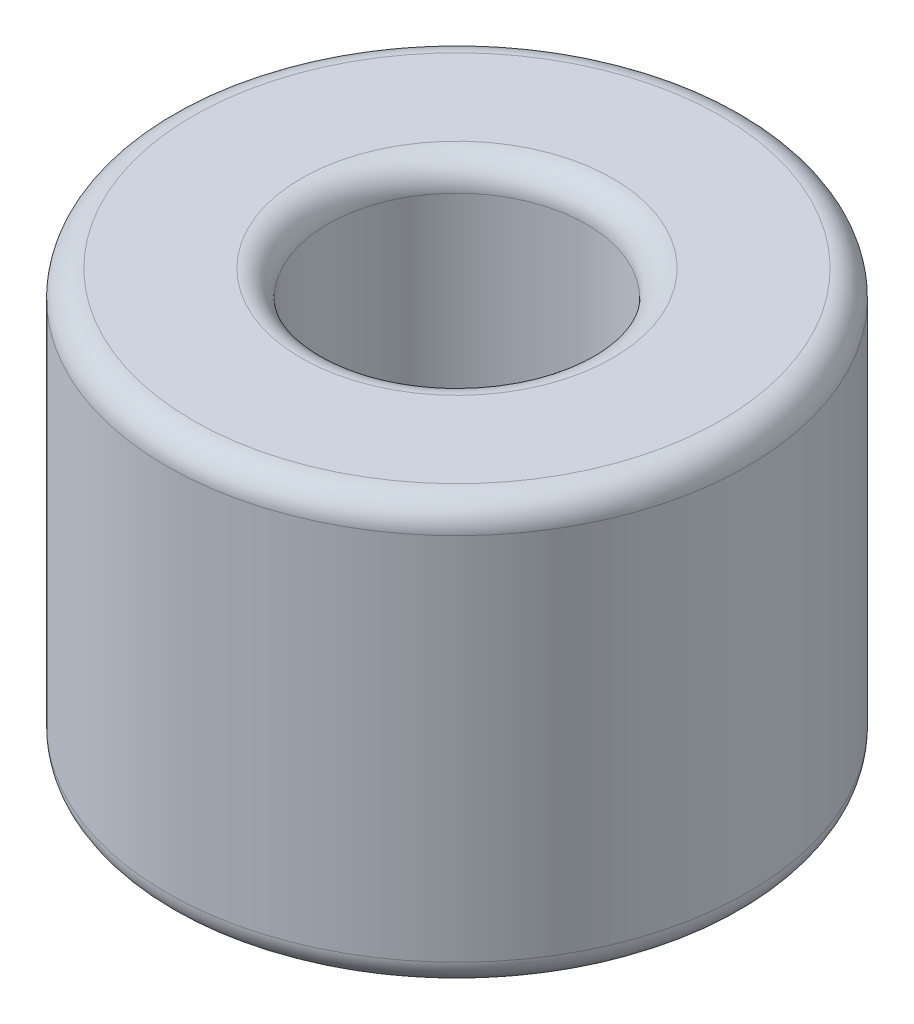
SolidWorks part; units mm, degrees
ref_plane "Front Plane" through (0, 0, 0) normal (0, 0, 1) x (1, 0, 0)
ref_plane "Top Plane" through (0, 0, 0) normal (0, 1, 0) x (1, 0, 0)
ref_plane "Right Plane" through (0, 0, 0) normal (1, 0, 0) x (0, 0, -1)
sketch "Sketch1" plane through (0, 0, 0) normal (0, 1, 0) x (1, 0, 0)
  circle A0 centre (0, 0) radius 5.5
  circle A1 centre (0, 0) radius 2.45
extrude "Boss-Extrude1" add sketch "Sketch1" along normal blind 8
fillet "Fillet3" radius 0.5 4 edges at (0, 0, 5.5) (0, 0, 2.45) (0, 8, 2.45) (0, 8, 5.5)
